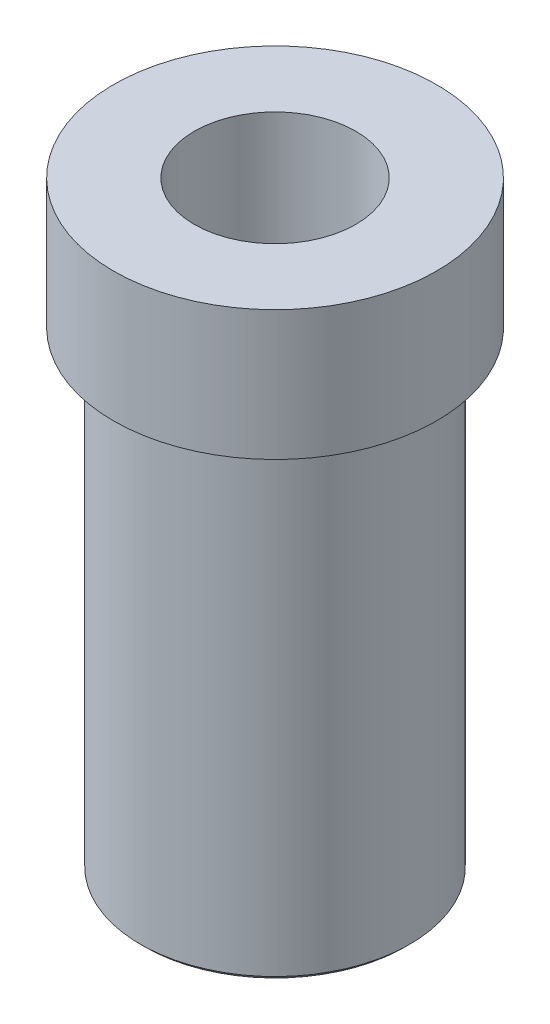
SolidWorks part; units mm, degrees
ref_plane "Front Plane" through (0, 0, 0) normal (0, 0, 1) x (1, 0, 0)
ref_plane "Top Plane" through (0, 0, 0) normal (0, 1, 0) x (1, 0, 0)
ref_plane "Right Plane" through (0, 0, 0) normal (1, 0, 0) x (0, 0, -1)
sketch "Sketch1" plane through (0, 0, 0) normal (0, 1, 0) x (1, 0, 0)
  circle A0 centre (0, 0) radius 4.7625
  dimension "D1" = 9.525
extrude "Boss-Extrude1" add sketch "Sketch1" along normal blind 3.5719 and the other way blind 0.254
sketch "Sketch2" plane through (0, -0.254, 0) normal (0, -1, 0) x (1, 0, 0)
  circle A0 centre (0, 0) radius 3.9688
  dimension "D1" = 7.9375
extrude "Boss-Extrude2" add sketch "Sketch2" along normal blind 13.8906
sketch "Sketch3" plane through (0, -14.1446, 0) normal (0, -1, 0) x (1, 0, 0)
  circle A0 centre (0, 0) radius 2.3813
  dimension "D1" = 4.7625
extrude "Cut-Extrude1" cut sketch "Sketch3" against normal through all
chamfer "Chamfer1" distance 0.127 angle 45 1 edges at (0, -14.1446, -3.9688)
